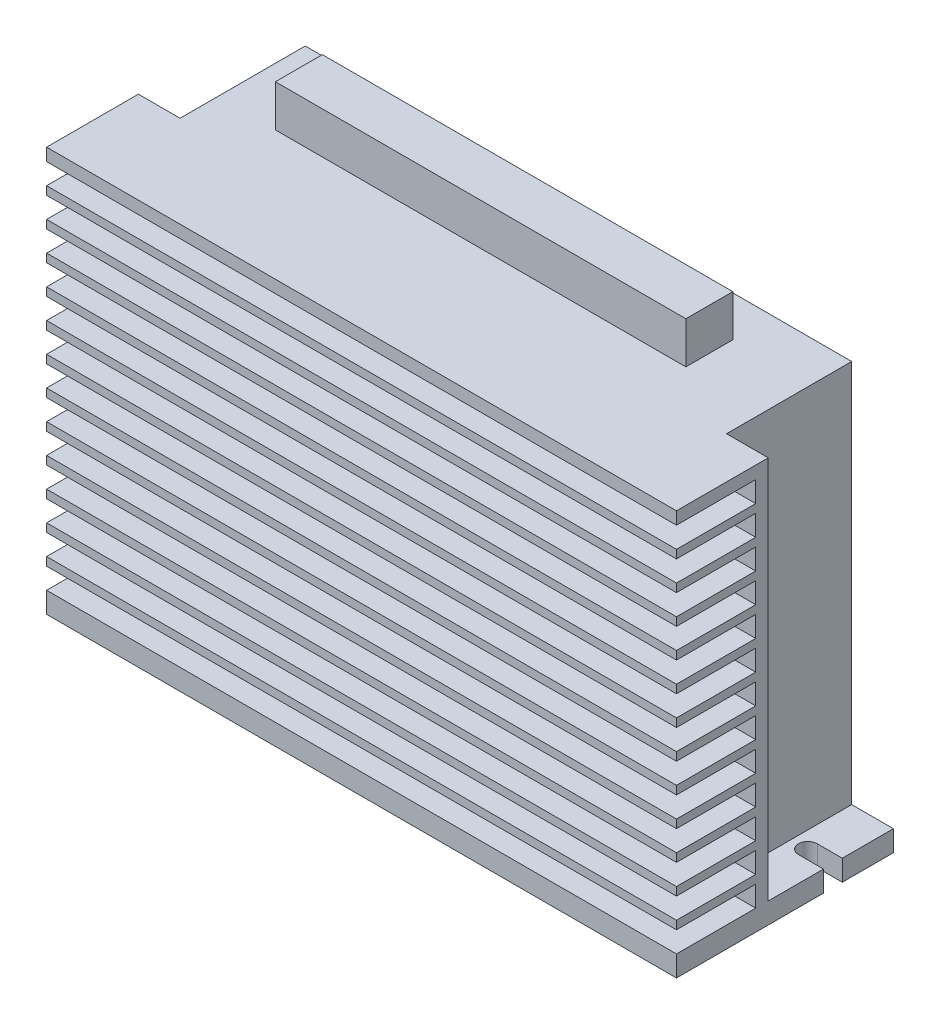
SolidWorks part; units mm, degrees
material "Nylon 6/10"
ref_plane "Front Plane" through (0, 0, 0) normal (0, 0, 1) x (1, 0, 0)
ref_plane "Top Plane" through (0, 0, 0) normal (0, 1, 0) x (1, 0, 0)
ref_plane "Right Plane" through (0, 0, 0) normal (1, 0, 0) x (0, 0, -1)
sketch "Sketch1" plane through (0, 0, 0) normal (0, 1, 0) x (1, 0, 0)
  line L1 (75.5, 26) -> (-75.5, 26)
  line L2 (75.5, 26) -> (75.5, -26)
  line L3 (75.5, -26) -> (-75.5, -26)
  line L4 (-75.5, 26) -> (-75.5, -26)
  line L5 (75.5, 26) -> (-75.5, -26) construction
  line L6 (75.5, -26) -> (-75.5, 26) construction
  point P0 (0, 0)
  dimension "D1" = 52
  dimension "D2" = 151
extrude "Boss-Extrude1" add sketch "Sketch1" along normal blind 92 and the other way blind 5
sketch "Sketch2" plane through (0, 0, 0) normal (0, 1, 0) x (1, 0, 0)
  line L1 (-75.5, 26) -> (-65.5, 26)
  line L2 (-75.5, 26) -> (-75.5, -4)
  line L3 (-75.5, -4) -> (-65.5, -4)
  line L4 (-65.5, 26) -> (-65.5, -4)
  line L5 (75.5, 26) -> (65.5, 26)
  line L6 (75.5, 26) -> (75.5, -4)
  line L7 (75.5, -4) -> (65.5, -4)
  line L8 (65.5, 26) -> (65.5, -4)
  dimension "D1" = 30
  dimension "D2" = 10
extrude "Cut-Extrude1" cut sketch "Sketch2" along normal up to next
sketch "Sketch3" plane through (0, 0, 0) normal (0, 1, 0) x (1, 0, 0)
  line L0 (-69.5, 11.5) -> (69.5, 11.5) construction
  line L1 (0, -28.6) -> (0, 28.6) construction
  line L2 (65.5, 26) -> (-65.5, 26) construction
  line L3 (-69.5, 9.25) -> (-75.5, 9.25)
  line L4 (-75.5, 26) -> (-75.5, -4) construction
  line L5 (-75.5, 9.25) -> (-75.5, 13.75)
  line L6 (-75.5, 13.75) -> (-69.5, 13.75)
  arc A0 (-69.5, 13.75) -> (-69.5, 9.25) centre (-69.5, 11.5) cw
  point P2 (0, 11.5)
  dimension "D1" = 139
  dimension "D2" = 14.5
  dimension "D3" = 4.5
extrude "Cut-Extrude2" cut sketch "Sketch3" against normal up to next
mirror "Mirror1" about plane through (0, 0, 0) normal (1, 0, 0) of "Cut-Extrude2"
sketch "Sketch4" plane through (0, 0, 0) normal (1, 0, 0) x (0, 0, -1)
  line L0 (-26, 0) -> (-7, 0)
  line L1 (-26, -5) -> (-26, 92) construction
  line L2 (-7, 0) -> (-7, 5)
  line L3 (-7, 5) -> (-26, 5)
  line L4 (-26, 5) -> (-26, 0)
  line L5 (-4, 92) -> (-4, 0) construction
  dimension "D1" = 5
  dimension "D2" = 3
extrude "Cut-Extrude3" cut sketch "Sketch4" against normal up to next and the other way up to next
pattern_linear "LPattern1" count 13 spacing 7 along (0, 1, 0) of "Cut-Extrude3"
sketch "Sketch5" plane through (0, 92, 0) normal (0, 1, 0) x (1, 0, 0)
  line L1 (-51.6561, 16.2568) -> (46.7502, 16.2568)
  line L2 (-51.6561, 16.2568) -> (-51.6561, 5.0021)
  line L3 (-51.6561, 5.0021) -> (46.7502, 5.0021)
  line L4 (46.7502, 16.2568) -> (46.7502, 5.0021)
extrude "Boss-Extrude2" add sketch "Sketch5" along normal blind 10
